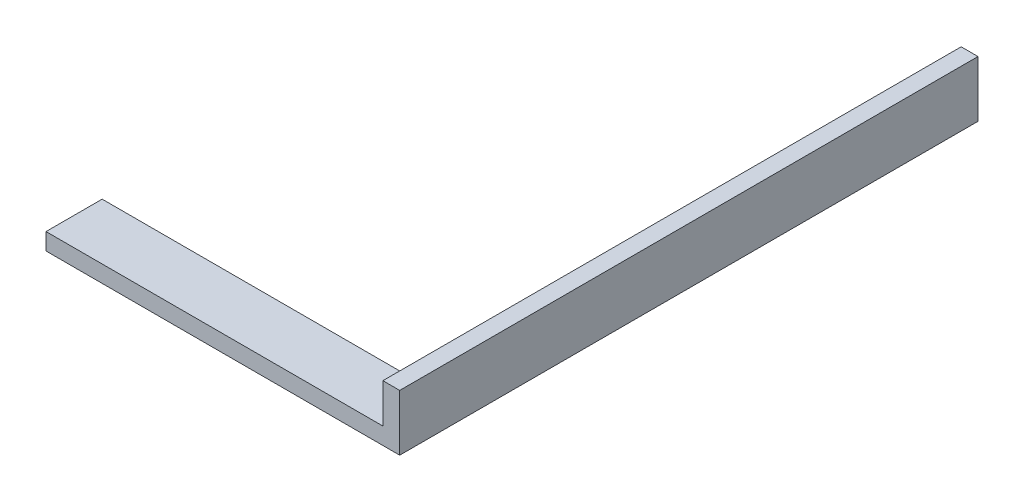
SolidWorks part; units mm, degrees
ref_plane "前视基准面" through (0, 0, 0) normal (0, 0, 1) x (1, 0, 0)
ref_plane "上视基准面" through (0, 0, 0) normal (0, 1, 0) x (1, 0, 0)
ref_plane "右视基准面" through (0, 0, 0) normal (1, 0, 0) x (0, 0, -1)
other "Configuration Table"
sketch "草图1" plane through (0, 0, 0) normal (0, 1, 0) x (1, 0, 0)
  line L1 (-31.5, -5) -> (31.5, -5)
  line L2 (-31.5, -5) -> (-31.5, 5)
  line L3 (-31.5, 5) -> (31.5, 5)
  line L4 (31.5, -5) -> (31.5, 5)
  line L5 (-31.5, -5) -> (31.5, 5) construction
  line L6 (-31.5, 5) -> (31.5, -5) construction
  point P0 (0, 0)
  dimension "D1" = 10
  dimension "D2" = 63
extrude "凸台-拉伸1" add sketch "草图1" along normal blind 2
sketch "草图4" plane through (0, 2, 0) normal (0, 1, 0) x (1, 0, 0)
  line L0 (-31.5, -5) -> (31.5, -5) construction
  line L1 (31.5, 5) -> (29.5, 5)
  line L2 (31.5, 5) -> (31.5, -5)
  line L3 (31.5, -5) -> (29.5, -5)
  line L4 (29.5, 5) -> (29.5, -5)
  dimension "D1" = 2
extrude "凸台-拉伸2" add sketch "草图4" along normal blind 93
sketch "草图5" plane through (0, 2, 0) normal (0, 1, 0) x (1, 0, 0)
  line L4 (29.5, -5) -> (29.5, 5)
  line L5 (29.5, 5) -> (-31.5, 5)
  line L6 (-31.5, 5) -> (-31.5, -5)
  line L7 (-31.5, -5) -> (29.5, -5)
  line L8 (29.5, -5) -> (29.5, 5)
  line L9 (29.5, 5) -> (-31.5, 5)
  line L10 (-31.5, 5) -> (-31.5, -5)
  line L11 (-31.5, -5) -> (29.5, -5)
  dimension "D1" = 0
extrude "凸台-拉伸3" add sketch "草图5" along normal blind 1
sketch "草图6" plane through (29.5, 0, 0) normal (-1, 0, 0) x (0, 0, 1)
  line L4 (-5, 95) -> (-5, 3)
  line L5 (-5, 3) -> (5, 3)
  line L6 (5, 3) -> (5, 95)
  line L7 (5, 95) -> (-5, 95)
  line L8 (-5, 95) -> (-5, 3)
  line L9 (-5, 3) -> (5, 3)
  line L10 (5, 3) -> (5, 95)
  line L11 (5, 95) -> (-5, 95)
  dimension "D1" = 0
extrude "凸台-拉伸4" add sketch "草图6" along normal blind 1
sketch "草图7" plane through (0, 0, -5) normal (0, 0, -1) x (-1, 0, 0)
  line L0 (-28.5, 95) -> (-28.5, 3) construction
  line L1 (-31.5, 0) -> (-28.5, 0)
  line L2 (-31.5, 0) -> (-31.5, 10)
  line L3 (-31.5, 10) -> (-28.5, 10)
  line L4 (-28.5, 0) -> (-28.5, 10)
  dimension "D1" = 10
extrude "凸台-拉伸5" add sketch "草图7" along normal blind 93
sketch "草图10" plane through (28.5, 0, 0) normal (-1, 0, 0) x (0, 0, 1)
  line L1 (-5, 10) -> (21.5943, 10)
  line L2 (-5, 10) -> (-5, 111.5597)
  line L3 (-5, 111.5597) -> (21.5943, 111.5597)
  line L4 (21.5943, 10) -> (21.5943, 111.5597)
extrude "切除-拉伸1" cut sketch "草图10" against normal blind 93
